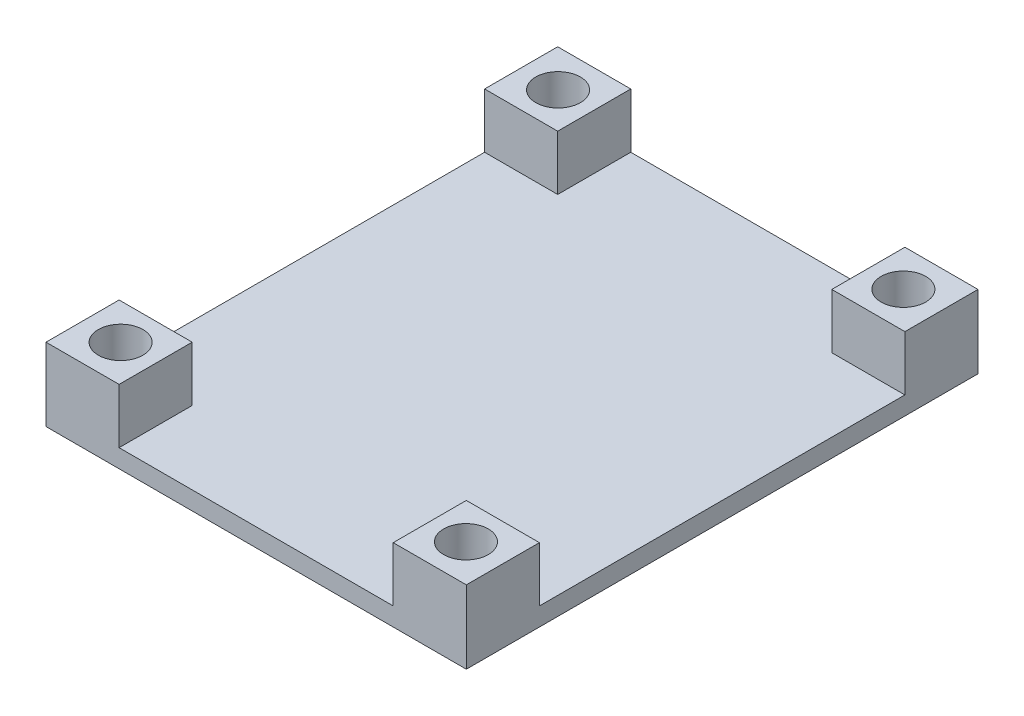
SolidWorks part; units mm, degrees
ref_plane "Front Plane" through (0, 0, 0) normal (0, 0, 1) x (1, 0, 0)
ref_plane "Top Plane" through (0, 0, 0) normal (0, 1, 0) x (1, 0, 0)
ref_plane "Right Plane" through (0, 0, 0) normal (1, 0, 0) x (0, 0, -1)
sketch "Sketch1" plane through (0, 0, 0) normal (0, 1, 0) x (1, 0, 0)
  line L0 (2.2113, 14.2748) -> (2.2113, -21.2852) construction
  line L1 (-12.3937, 14.2748) -> (16.8163, 14.2748)
  line L2 (-12.3937, 14.2748) -> (-12.3937, -21.2852)
  line L3 (-12.3937, -21.2852) -> (16.8163, -21.2852)
  line L4 (16.8163, 14.2748) -> (16.8163, -21.2852)
  line L5 (-12.3937, -3.5052) -> (16.8163, -3.5052) construction
  circle A0 centre (-9.7887, 11.6948) radius 1.55
  circle A1 centre (14.2113, 11.6948) radius 1.55
  circle A2 centre (14.2113, -18.7052) radius 1.55
  circle A3 centre (-9.7887, -18.7052) radius 1.55
  dimension "D3" = 3.1
  dimension "D4" = 3.1
  dimension "D5" = 3.1
  dimension "D6" = 3.1
  dimension "D1" = 29.21
  dimension "D2" = 35.56
  dimension "D7" = 24
  dimension "D8" = 30.4
  dimension "D9" = 15.2
  dimension "D10" = 12
extrude "Boss-Extrude1" add sketch "Sketch1" along normal blind 5.08
sketch "Sketch2" plane through (0, 5.08, 0) normal (0, 1, 0) x (1, 0, 0)
  line L0 (-12.3937, 14.2748) -> (-12.3937, -21.2852) construction
  line L1 (-7.3137, 9.1948) -> (11.7363, 9.1948)
  line L2 (-7.3137, 9.1948) -> (-7.3137, -16.2052)
  line L3 (-7.3137, -16.2052) -> (11.7363, -16.2052)
  line L4 (11.7363, 9.1948) -> (11.7363, -16.2052)
  line L5 (16.8163, -21.2852) -> (16.8163, 14.2748) construction
  line L6 (16.8163, 14.2748) -> (-12.3937, 14.2748) construction
  line L7 (-12.3937, -21.2852) -> (16.8163, -21.2852) construction
  line L9 (-7.3137, 9.1948) -> (-12.3937, 9.1948)
  line L10 (-7.3137, 9.1948) -> (-7.3137, -16.2052)
  line L11 (-7.3137, -16.2052) -> (-12.3937, -16.2052)
  line L12 (-12.3937, 9.1948) -> (-12.3937, -16.2052)
  line L13 (-7.3137, 9.1948) -> (11.7363, 9.1948)
  line L14 (-7.3137, 9.1948) -> (-7.3137, 14.2748)
  line L15 (-7.3137, 14.2748) -> (11.7363, 14.2748)
  line L16 (11.7363, 9.1948) -> (11.7363, 14.2748)
  line L17 (11.7363, 9.1948) -> (16.8163, 9.1948)
  line L18 (11.7363, 9.1948) -> (11.7363, -16.2052)
  line L19 (11.7363, -16.2052) -> (16.8163, -16.2052)
  line L20 (16.8163, 9.1948) -> (16.8163, -16.2052)
  line L21 (11.7363, -16.2052) -> (-7.3137, -16.2052)
  line L22 (11.7363, -16.2052) -> (11.7363, -21.2852)
  line L23 (11.7363, -21.2852) -> (-7.3137, -21.2852)
  line L24 (-7.3137, -16.2052) -> (-7.3137, -21.2852)
  line M7 (-12.3937, 14.2748) -> (-12.3937, -21.2852)
  line M8 (-12.3937, -21.2852) -> (16.8163, -21.2852)
  line M9 (16.8163, -21.2852) -> (16.8163, 14.2748)
  line M10 (16.8163, 14.2748) -> (-12.3937, 14.2748)
  dimension "D1" = 5.08
  dimension "D2" = 5.08
  dimension "D3" = 5.08
  dimension "D4" = 5.08
extrude "Cut-Extrude1" cut sketch "Sketch2" against normal blind 3.81 contours L11 L2 L9 M7 | L1 L16 L14 M10 | L4 L19 L17 M9 | L4 L1 L2 L3 | L3 L24 L22 M8
